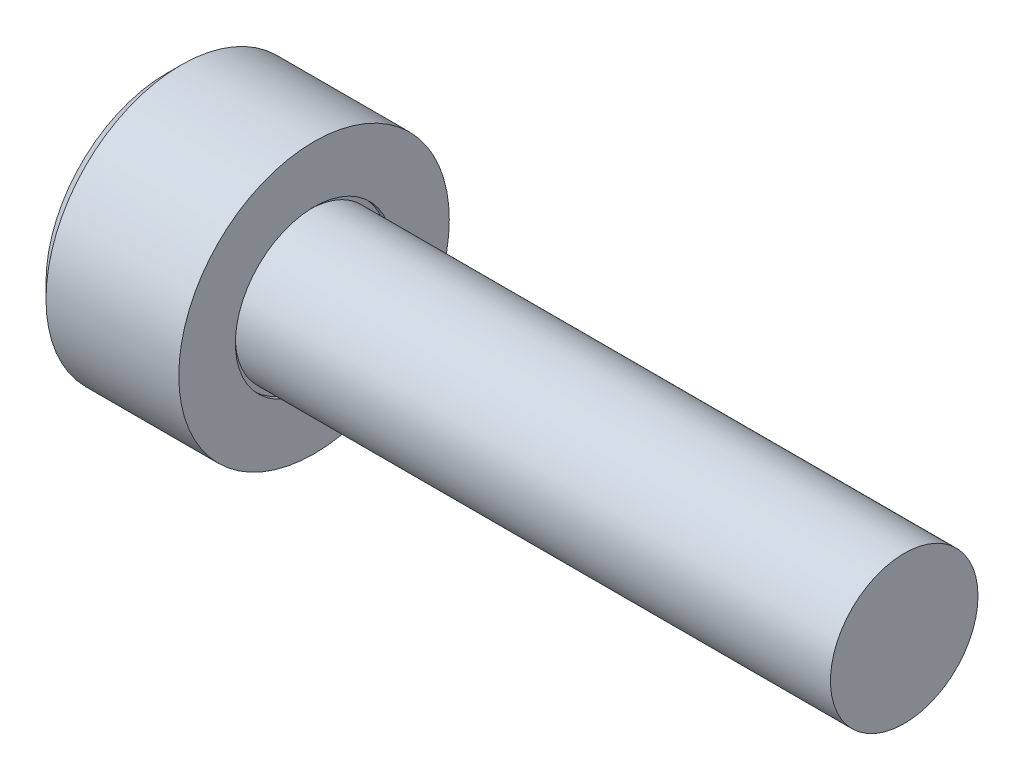
SolidWorks part; units mm, degrees
material "ｽﾃﾝﾚｽ鋼(ｸﾛﾑ)"
ref_plane "正面" through (0, 0, 0) normal (0, 0, 1) x (1, 0, 0)
ref_plane "平面" through (0, 0, 0) normal (0, 1, 0) x (1, 0, 0)
ref_plane "右側面" through (0, 0, 0) normal (1, 0, 0) x (0, 0, -1)
sketch "ｽｹｯﾁ1" plane through (0, 0, 0) normal (0, 0, 1) x (1, 0, 0)
  line L0 (-3, 2.75) -> (-3, 0)
  line L1 (-3, 0) -> (0, 0)
  line L2 (0, 0) -> (0, 2.75)
  line L3 (0, 2.75) -> (-3, 2.75)
  line L4 (-3, 0) -> (0, 0) construction
  dimension "D1" = 2.75
  dimension "D2" = 3
revolve "回転1" add sketch "ｽｹｯﾁ1" angle 360 about L4
sketch "ｽｹｯﾁ2" plane through (0, 0, 0) normal (1, 0, 0) x (0, 0, -1)
  circle A0 centre (0, 0) radius 1.5
  dimension "D1" = 3
extrude "ﾎﾞｽ - 押し出し1" add sketch "ｽｹｯﾁ2" along normal blind 100
sketch "ｽｹｯﾁ3" plane through (-3, 0, 0) normal (-1, 0, 0) x (0, 0, 1)
  line L0 (-0.72, -1.2471) -> (0.72, -1.2471)
  line L1 (0.72, -1.2471) -> (1.44, 0)
  line L2 (1.44, 0) -> (0.72, 1.2471)
  line L3 (0.72, 1.2471) -> (-0.72, 1.2471)
  line L4 (-0.72, 1.2471) -> (-1.44, 0)
  line L5 (-1.44, 0) -> (-0.72, -1.2471)
  circle A0 centre (0, 0) radius 1.44 construction
  dimension "D1" = 2.88
extrude "ｶｯﾄ - 押し出し1" cut sketch "ｽｹｯﾁ3" against normal blind 1.5
sketch "ｽｹｯﾁ4" plane through (0, 0, 0) normal (0, 0, 1) x (1, 0, 0)
  line L0 (-1.5, 1.2471) -> (-1.5, 0)
  line L1 (-1.5, 0) -> (-1.1651, 0)
  line L2 (-1.1651, 0) -> (-1.5, 1.2471)
  line L3 (-1.5, 0) -> (-1.165, 0) construction
  line L4 (-1.5, 0) -> (-1.5, -1.2471) construction
  line L5 (-1.5, 1.2471) -> (-3.7676, 1.2471) construction
  dimension "D1" = 0.3349
revolve "ｶｯﾄ - 回転1" cut sketch "ｽｹｯﾁ4" angle 360 about L3
chamfer "面取り1" distance 0.3 angle 45 2 edges at (100, 0, -1.5) (-3, 0, -2.75)
ref_plane "平面1" through (5, 0, 0) normal (1, 0, 0) x (0, 0, -1)
ref_plane "平面2" through (10, 0, 0) normal (1, 0, 0) x (0, 0, -1)
ref_plane "平面3" through (15, 0, 0) normal (1, 0, 0) x (0, 0, -1)
ref_plane "平面4" through (20, 0, 0) normal (1, 0, 0) x (0, 0, -1)
ref_plane "平面5" through (25, 0, 0) normal (1, 0, 0) x (0, 0, -1)
ref_plane "平面6" through (30, 0, 0) normal (1, 0, 0) x (0, 0, -1)
ref_plane "平面7" through (35, 0, 0) normal (1, 0, 0) x (0, 0, -1)
ref_plane "平面8" through (40, 0, 0) normal (1, 0, 0) x (0, 0, -1)
ref_plane "平面9" through (45, 0, 0) normal (1, 0, 0) x (0, 0, -1)
ref_plane "平面10" through (50, 0, 0) normal (1, 0, 0) x (0, 0, -1)
ref_plane "平面11" through (55, 0, 0) normal (1, 0, 0) x (0, 0, -1)
ref_plane "平面12" through (60, 0, 0) normal (1, 0, 0) x (0, 0, -1)
ref_plane "平面13" through (65, 0, 0) normal (1, 0, 0) x (0, 0, -1)
ref_plane "平面14" through (70, 0, 0) normal (1, 0, 0) x (0, 0, -1)
ref_plane "平面15" through (75, 0, 0) normal (1, 0, 0) x (0, 0, -1)
ref_plane "平面16" through (80, 0, 0) normal (1, 0, 0) x (0, 0, -1)
ref_plane "平面17" through (85, 0, 0) normal (1, 0, 0) x (0, 0, -1)
ref_plane "平面18" through (90, 0, 0) normal (1, 0, 0) x (0, 0, -1)
ref_plane "平面19" through (95, 0, 0) normal (1, 0, 0) x (0, 0, -1)
ref_plane "平面20" through (100, 0, 0) normal (1, 0, 0) x (0, 0, -1)
other "ｻｰﾌｪｽ ｶｯﾄ1" [suppressed]
other "ｻｰﾌｪｽ ｶｯﾄ2" [suppressed]
other "ｻｰﾌｪｽ ｶｯﾄ3" [suppressed]
other "ｻｰﾌｪｽ ｶｯﾄ4" [suppressed]
other "ｻｰﾌｪｽ ｶｯﾄ5" [suppressed]
other "ｻｰﾌｪｽ ｶｯﾄ6" [suppressed]
other "ｻｰﾌｪｽ ｶｯﾄ7" [suppressed]
other "ｻｰﾌｪｽ ｶｯﾄ8" [suppressed]
other "ｻｰﾌｪｽ ｶｯﾄ9" [suppressed]
other "ｻｰﾌｪｽ ｶｯﾄ11" [suppressed]
other "ｻｰﾌｪｽ ｶｯﾄ12" [suppressed]
sketch "ｽｹｯﾁ5" plane through (0, 0, 0) normal (1, 0, 0) x (0, 0, -1)
  circle A0 centre (0, 0) radius 1.6
  circle A1 centre (0, 0) radius 1.5 construction
  circle A2 centre (0, 0) radius 1.5
  dimension "D1" = 3.2
extrude "ｶｯﾄ - 押し出し2" cut sketch "ｽｹｯﾁ5" against normal blind 0.1
ref_plane "平面21" through (8, 0, 0) normal (1, 0, 0) x (0, 0, -1)
ref_plane "平面22" through (12, 0, 0) normal (1, 0, 0) x (0, 0, -1)
other "ｻｰﾌｪｽ ｶｯﾄ13" [suppressed]
other "ｻｰﾌｪｽ ｶｯﾄ14"
ref_plane "平面23" [suppressed] through (6, 0, 0) normal (1, 0, 0) x (0, 0, -1)
other "ｻｰﾌｪｽ ｶｯﾄ15" [suppressed]
